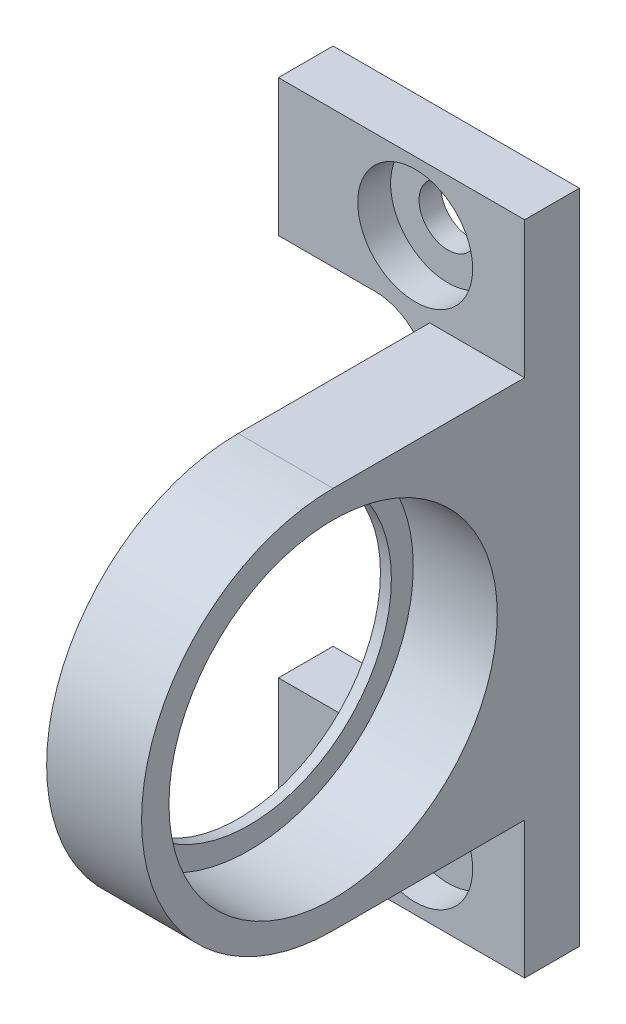
SolidWorks part; units mm, degrees
ref_plane "前视基准面" through (0, 0, 0) normal (0, 0, 1) x (1, 0, 0)
ref_plane "上视基准面" through (0, 0, 0) normal (0, 1, 0) x (1, 0, 0)
ref_plane "右视基准面" through (0, 0, 0) normal (1, 0, 0) x (0, 0, -1)
sketch "草图2" plane through (0, 0, 0) normal (0, 0, 1) x (1, 0, 0)
  line L0 (-14.7736, 24.3382) -> (-14.7736, -35.6618)
  line L1 (-14.7736, -35.6618) -> (30.2264, -35.6618)
  line L2 (7.7264, -35.6618) -> (7.7264, -23.1618)
  line L3 (21.55, -23.1618) -> (-6.0971, -23.1618)
  line L4 (-6.0971, -23.1618) -> (-6.0971, 11.8382)
  line L5 (-6.0971, 11.8382) -> (21.55, 11.8382)
  line L6 (7.7264, 11.8382) -> (7.7264, 24.3382)
  line L7 (30.2264, 24.3382) -> (-14.7736, 24.3382)
  line L8 (7.7264, 28.8603) -> (7.7264, -39.8897) construction
  line L9 (21.55, -23.1618) -> (21.55, 11.8382)
  line L10 (30.2264, 24.3382) -> (30.2264, -35.6618)
  line L11 (-18.1559, -5.6618) -> (33.2411, -5.6618) construction
  point P16 (-6.0971, -5.6618)
  point P17 (-14.7736, -5.6618)
  dimension "D1" = 45
  dimension "D2" = 35
  dimension "D3" = 60
extrude "凸台-拉伸2" add sketch "草图2" along normal blind 5 contours L6 L7 L0 L1 L2 L3 L4 L5 | L10 L7 L6 L5 L9 L3 L2 L1
sketch "草图4" plane through (0, 0, 5) normal (0, 0, 1) x (1, 0, 0)
  line L0 (-18.165, -5.6618) -> (33.9165, -5.6618) construction
  line L1 (-14.7736, 24.3382) -> (-14.7736, -35.6618) construction
  line L2 (-14.7736, -23.1618) -> (-6.0971, -23.1618)
  line L3 (-14.7736, -23.1618) -> (-14.7736, 11.8382)
  line L4 (-14.7736, 11.8382) -> (-6.0971, 11.8382)
  line L5 (-6.0971, -23.1618) -> (-6.0971, 11.8382)
  line L6 (-6.0971, -23.1618) -> (-6.0971, 11.8382) construction
  line L7 (7.7264, -39.813) -> (7.7264, 28.1228) construction
  line L8 (30.2264, 11.8382) -> (21.55, 11.8382)
  line L9 (21.55, -23.1618) -> (21.55, 11.8382)
  line L10 (30.2264, -23.1618) -> (21.55, -23.1618)
  line L11 (30.2264, -23.1618) -> (30.2264, 11.8382)
  point P17 (-14.7736, -5.6618)
  dimension "D1" = 35
extrude "凸台-拉伸15" add sketch "草图4" along normal blind 35
sketch "草图5" plane through (-14.7736, 0, 0) normal (-1, 0, 0) x (0, 0, 1)
  line L0 (0, -5.6618) -> (40, -5.6618)
  line L1 (0, 24.3382) -> (0, -35.6618) construction
  line L2 (40, 11.8382) -> (40, -23.1618) construction
  line L3 (22.5, 11.8382) -> (40, 11.8382)
  line L4 (40, 11.8382) -> (40, -23.1618)
  line L5 (40, -23.1618) -> (22.5, -23.1618)
  circle A0 centre (22.5, -5.6618) radius 17.5
  line M5 (5, -23.1618) -> (40, -23.1618)
  line M6 (40, -23.1618) -> (40, 11.8382)
  line M7 (40, 11.8382) -> (5, 11.8382)
  dimension "D1" = 35
extrude "切除-拉伸1" cut sketch "草图5" against normal blind 45 contours A0 M5 M6 | A0 M6 M7
sketch "草图6" plane through (-14.7736, 0, 0) normal (-1, 0, 0) x (0, 0, 1)
  circle A0 centre (22.5, -5.6618) radius 15
extrude "切除-拉伸2" cut sketch "草图6" against normal blind 45
fillet "圆角1" radius 5 4 edges at (-6.0971, 11.8382, 2.5) (21.55, 11.8382, 2.5) (-6.0971, -23.1618, 2.5) (21.55, -23.1618, 2.5)
sketch "草图7" plane through (-6.0971, 0, 0) normal (1, 0, 0) x (0, 0, -1)
  circle A0 centre (-22.5, -5.6618) radius 15
  circle A1 centre (-22.5, -5.6618) radius 13
extrude "凸台-拉伸16" add sketch "草图7" against normal blind 1
sketch "草图8" plane through (21.55, 0, 0) normal (-1, 0, 0) x (0, 0, 1)
  circle A0 centre (22.5, -5.6618) radius 15
  circle A1 centre (22.5, -5.6618) radius 13
extrude "凸台-拉伸17" add sketch "草图8" against normal blind 1
sketch "草图9" plane through (0, 0, 5) normal (0, 0, 1) x (1, 0, 0)
  line L0 (7.7264, 24.3382) -> (7.7264, -35.6618)
  line L13 (30.2264, 24.3382) -> (-14.7736, 24.3382) construction
  line L14 (-14.7736, -35.6618) -> (30.2264, -35.6618) construction
sketch "草图11" plane through (0, 0, 5) normal (0, 0, 1) x (1, 0, 0)
  line L0 (-14.7736, 18.0882) -> (30.2264, 18.0882)
  line L1 (-14.7736, 24.3382) -> (-14.7736, 11.8382) construction
  line L2 (30.2264, 24.3382) -> (30.2264, 11.8382) construction
  line L3 (7.7264, 24.3382) -> (7.7264, -35.6618) construction
  line L4 (30.2264, 24.3382) -> (-14.7736, 24.3382) construction
  line L5 (-14.7736, -35.6618) -> (30.2264, -35.6618) construction
  line L6 (7.7264, -5.6618) -> (45.6912, -5.6618) construction
  line L10 (-14.7736, -29.4118) -> (30.2264, -29.4118)
  line L11 (-14.7736, -23.1618) -> (-14.7736, -35.6618) construction
  point P4 (-4.7736, 18.0882)
  point P7 (0, 0)
  point P16 (-4.7736, -29.4118)
  point P18 (20.2264, -29.4118)
  point P25 (20.2264, 18.0882)
  dimension "D1" = 10
split "分割1" trim tools "草图9" bodies to split 112 resulting bodies 117 118
delete or keep bodies "实体-删除/保留 2" type delete bodies bodies 117
hole_wizard "大小平盘开槽螺钉柱孔1" positions "3D草图3" profile "草图14" counterbore size "M5" standard "AS" end condition through all
sketch3d "3D草图3"
  point P0 (20.2264, -29.4118, 5)
  point P3 (20.2264, 18.0882, 5)
sketch "草图14" plane through (20.2264, -29.4118, 5) normal (1, 0, 0) x (0, -1, 0)
  line L0 (0, 0) -> (0, 5)
  line L1 (0, 5) -> (2.65, 5)
  line L3 (2.65, 5) -> (2.65, 3)
  line L4 (2.65, 3) -> (5.25, 3)
  line L5 (5.25, 3) -> (5.25, 0)
  line L7 (5.25, 0) -> (0, 0)
  line L11 (0, -6.35) -> (0, 107.95) construction
  dimension "通孔孔直径" = 5.3
  dimension "通孔孔深度" = 5
  dimension "柱形沉头孔直径" = 10.5
  dimension "柱形沉头孔深度" = 3
